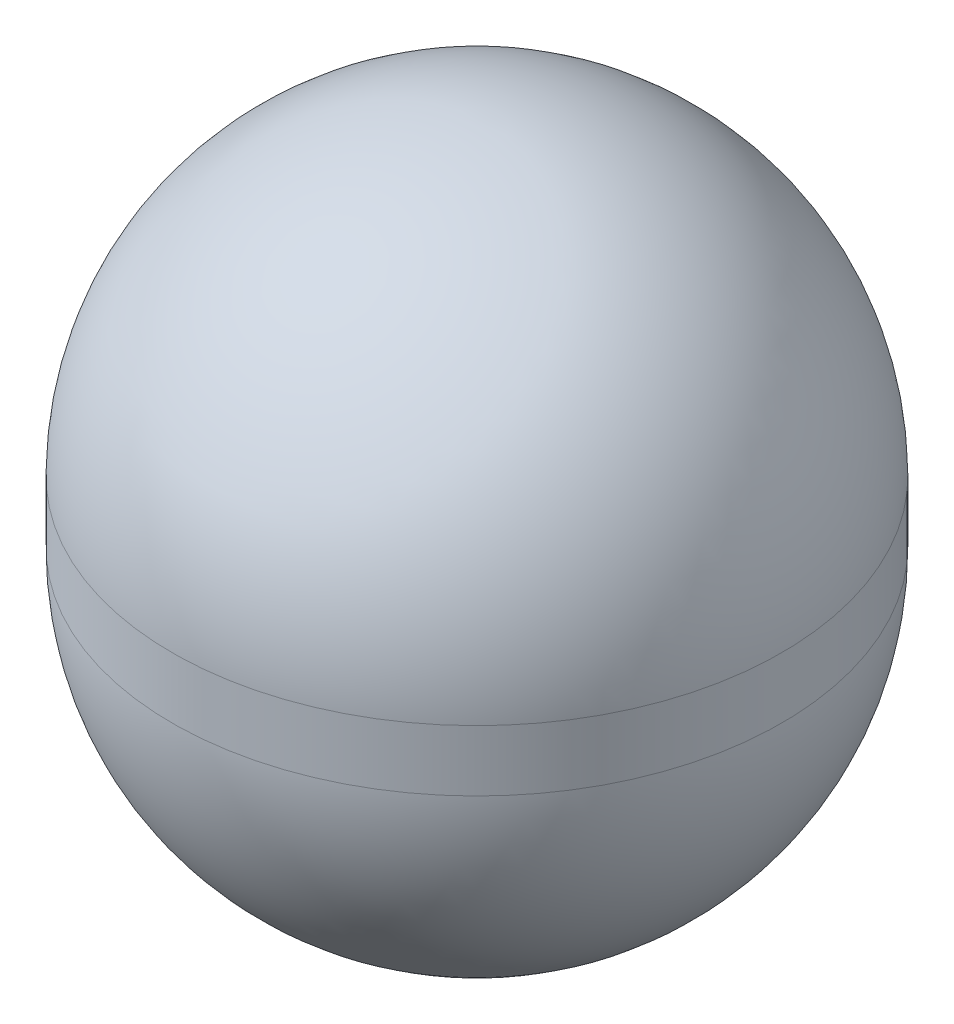
SolidWorks part; units mm, degrees
ref_plane "Front Plane" through (0, 0, 0) normal (0, 0, 1) x (1, 0, 0)
ref_plane "Top Plane" through (0, 0, 0) normal (0, 1, 0) x (1, 0, 0)
ref_plane "Right Plane" through (0, 0, 0) normal (1, 0, 0) x (0, 0, -1)
sketch "Sketch1" plane through (0, 0, 0) normal (0, 1, 0) x (1, 0, 0)
  line L0 (0, -12.7) -> (0, 12.7) construction
  line L1 (0, -12.7) -> (0, 12.7)
  arc A0 (0, -12.7) -> (0, 12.7) centre (0, 0) ccw
  point P5 (0, 12.7)
revolve "Revolve2" add sketch "Sketch1" angle 180 about L0
sketch "Sketch2" plane through (0, 0, 0) normal (0, 1, 0) x (1, 0, 0)
  circle A0 centre (0, 0) radius 12.7
extrude "Boss-Extrude1" add sketch "Sketch2" along normal blind 2.54
sketch "Sketch3" plane through (0, 2.54, 0) normal (0, 1, 0) x (1, 0, 0)
  line L0 (0, 12.7) -> (0, -12.7) construction
  line L1 (0, 12.7) -> (0, -12.7)
  arc A0 (0, 12.7) -> (0, -12.7) centre (0, 0) cw
  circle A1 centre (0, 0) radius 12.7 construction
revolve "Revolve3" add sketch "Sketch3" angle 180 about L0
